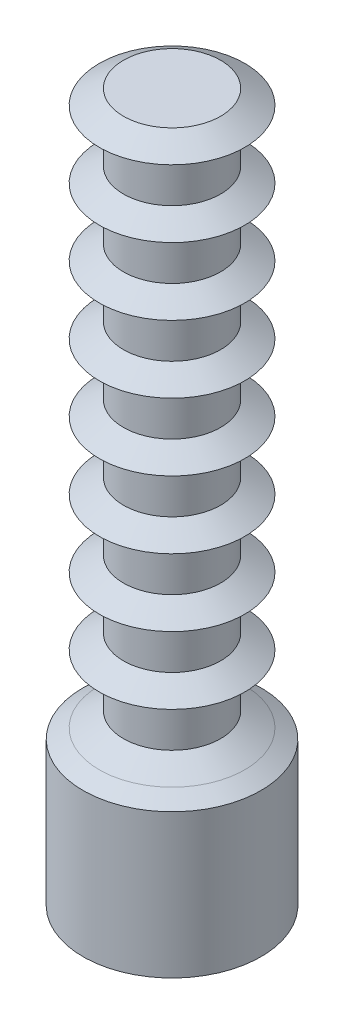
SolidWorks part; units mm, degrees
ref_plane "Front Plane" through (0, 0, 0) normal (0, 0, 1) x (1, 0, 0)
ref_plane "Top Plane" through (0, 0, 0) normal (0, 1, 0) x (1, 0, 0)
ref_plane "Right Plane" through (0, 0, 0) normal (1, 0, 0) x (0, 0, -1)
sketch "Sketch1" plane through (0, 0, 0) normal (0, 0, 1) x (1, 0, 0)
  line L0 (-2.9316, 34.2) -> (-2.9316, 31.2) construction
  line L1 (-1.2316, 0) -> (-5.4316, 0)
  line L2 (-5.4316, 34.2) -> (-5.4316, 0) construction
  line L3 (-5.4316, 0) -> (-5.4316, 33.4)
  line L5 (-3.1389, 32.0142) -> (-1.9958, 32.7)
  line L7 (-5.4316, 33.4) -> (-3.1389, 33.4)
  line L9 (-2.6564, 33.1045) -> (-3.1389, 33.4)
  line L10 (-3.1389, 33.4) -> (-1.9958, 32.7)
  line L12 (-3.1389, 28.8342) -> (-1.9958, 29.52)
  line L13 (-3.1389, 25.6542) -> (-1.9958, 26.34)
  line L14 (-3.1389, 30.22) -> (-3.1389, 32.0142)
  line L15 (-3.1389, 22.4742) -> (-1.9958, 23.16)
  line L17 (-3.1389, 19.2942) -> (-1.9958, 19.98)
  line L18 (-3.1389, 30.22) -> (-1.9958, 29.52)
  line L20 (-3.1389, 16.1142) -> (-1.9958, 16.8)
  line L22 (-3.1389, 27.04) -> (-3.1389, 28.8342)
  line L24 (-3.1389, 27.04) -> (-1.9958, 26.34)
  line L26 (-3.1389, 12.9342) -> (-1.9958, 13.62)
  line L28 (-3.1389, 23.86) -> (-3.1389, 25.6542)
  line L29 (-2.9316, 34.2) -> (-2.9316, 30.7) construction
  line L32 (-3.1389, 9.7542) -> (-1.9958, 10.44)
  line L33 (-3.1389, 23.86) -> (-1.9958, 23.16)
  line L38 (-3.1389, 20.68) -> (-3.1389, 22.4742)
  line L40 (-3.1389, 20.68) -> (-1.9958, 19.98)
  line L44 (-3.1389, 17.5) -> (-3.1389, 19.2942)
  line L46 (-3.1389, 17.5) -> (-1.9958, 16.8)
  line L50 (-3.1389, 14.32) -> (-3.1389, 16.1142)
  line L52 (-3.1389, 14.32) -> (-1.9958, 13.62)
  line L56 (-3.1389, 11.14) -> (-3.1389, 12.9342)
  line L58 (-3.1389, 11.14) -> (-1.9958, 10.44)
  line L60 (-1.9958, 10.44) -> (-3.1543, 9.7449)
  line L62 (-3.1389, 7.96) -> (-3.1389, 9.7542)
  line L71 (-3.1389, 7.96) -> (-1.9958, 7.26)
  line L75 (-1.2316, 0) -> (-1.2316, 6.796)
  line L76 (-1.9958, 7.26) -> (-1.2316, 6.796)
  point P9 (-2.9316, 32.7)
  dimension "D2" = 3
  dimension "D3" = 2.5
  dimension "D6" = 0.8
revolve "Revolve2" add sketch "Sketch1" angle 360 about L2
